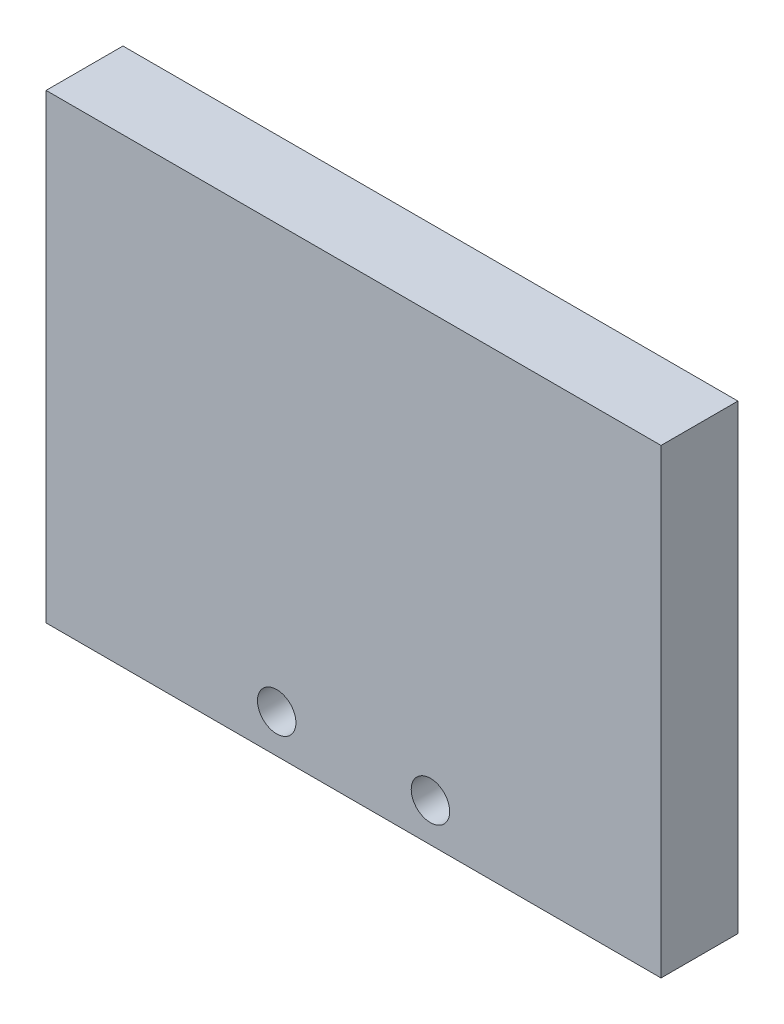
SolidWorks part; units mm, degrees
ref_plane "Front Plane" through (0, 0, 0) normal (0, 0, 1) x (1, 0, 0)
ref_plane "Top Plane" through (0, 0, 0) normal (0, 1, 0) x (1, 0, 0)
ref_plane "Right Plane" through (0, 0, 0) normal (1, 0, 0) x (0, 0, -1)
sketch "Sketch1" plane through (0, 0, 0) normal (0, 0, 1) x (1, 0, 0)
  line L1 (-57.5851, 19.8139) -> (22.4149, 19.8139)
  line L2 (-57.5851, 19.8139) -> (-57.5851, -40.1861)
  line L3 (-57.5851, -40.1861) -> (22.4149, -40.1861)
  line L4 (22.4149, 19.8139) -> (22.4149, -40.1861)
  dimension "D1" = 80
  dimension "D2" = 60
extrude "Boss-Extrude1" add sketch "Sketch1" along normal blind 10
sketch "Sketch2" plane through (0, 0, 10) normal (0, 0, 1) x (1, 0, 0)
  line L0 (-17.5851, 19.8139) -> (-17.5851, -40.1861) construction
  line L1 (22.4149, 19.8139) -> (-57.5851, 19.8139) construction
  line L2 (-57.5851, -40.1861) -> (22.4149, -40.1861) construction
  circle A0 centre (-27.5851, -35.1861) radius 2.5
  circle A1 centre (-7.5851, -35.1861) radius 2.5
  dimension "D1" = 5
  dimension "D2" = 20
  dimension "D3" = 5
extrude "Cut-Extrude1" cut sketch "Sketch2" against normal blind 10
sketch "Sketch3" plane through (0, 0, 10) normal (0, 0, 1) x (1, 0, 0)
  line L0 (-22.5851, -5.6861) -> (-12.5851, -5.6861)
  line L1 (22.4149, 19.8139) -> (-57.5851, 19.8139) construction
  line L2 (-22.5851, -6.1861) -> (-12.5851, -6.1861)
  line L3 (-22.5851, -6.6861) -> (-12.5851, -6.6861)
  line L4 (-22.5851, -7.1861) -> (-12.5851, -7.1861)
  line L5 (-22.5851, -7.6861) -> (-12.5851, -7.6861)
  line L6 (-22.5851, -8.1861) -> (-12.5851, -8.1861)
  line L7 (-22.5851, -8.6861) -> (-12.5851, -8.6861)
  line L8 (-22.5851, -9.1861) -> (-12.5851, -9.1861)
  line L9 (-22.5851, -9.6861) -> (-12.5851, -9.6861)
  line L10 (-22.5851, -10.1861) -> (-12.5851, -10.1861)
  line L11 (-22.5851, -10.6861) -> (-12.5851, -10.6861)
  line L12 (-22.5851, -11.1861) -> (-12.5851, -11.1861)
  line L13 (-22.5851, -11.6861) -> (-12.5851, -11.6861)
  line L14 (-22.5851, -12.1861) -> (-12.5851, -12.1861)
  line L15 (-22.5851, -12.6861) -> (-12.5851, -12.6861)
  line L16 (-22.5851, -13.1861) -> (-12.5851, -13.1861)
  line L17 (-22.5851, -13.6861) -> (-12.5851, -13.6861)
  line L18 (-22.5851, -14.1861) -> (-12.5851, -14.1861)
  line L19 (-22.5851, -14.6861) -> (-12.5851, -14.6861)
  line L20 (-22.5851, -15.1861) -> (-12.5851, -15.1861)
  line L21 (-57.5851, -10.1861) -> (22.4149, -10.1861) construction
  line L22 (-57.5851, 19.8139) -> (-57.5851, -40.1861) construction
  line L23 (22.4149, -40.1861) -> (22.4149, 19.8139) construction
  line L24 (-22.5851, -5.1861) -> (-22.5851, -15.1861)
  line L25 (-22.0851, -5.1861) -> (-22.0851, -15.1861)
  line L26 (-21.5851, -5.1861) -> (-21.5851, -15.1861)
  line L27 (-21.0851, -5.1861) -> (-21.0851, -15.1861)
  line L28 (-20.5851, -5.1861) -> (-20.5851, -15.1861)
  line L29 (-20.0851, -5.1861) -> (-20.0851, -15.1861)
  line L30 (-19.5851, -5.1861) -> (-19.5851, -15.1861)
  line L31 (-19.0851, -5.1861) -> (-19.0851, -15.1861)
  line L32 (-18.5851, -5.1861) -> (-18.5851, -15.1861)
  line L33 (-18.0851, -5.1861) -> (-18.0851, -15.1861)
  line L34 (-17.5851, -5.1861) -> (-17.5851, -15.1861)
  line L35 (-17.0851, -5.1861) -> (-17.0851, -15.1861)
  line L36 (-16.5851, -5.1861) -> (-16.5851, -15.1861)
  line L37 (-16.0851, -5.1861) -> (-16.0851, -15.1861)
  line L38 (-15.5851, -5.1861) -> (-15.5851, -15.1861)
  line L39 (-15.0851, -5.1861) -> (-15.0851, -15.1861)
  line L40 (-14.5851, -5.1861) -> (-14.5851, -15.1861)
  line L41 (-14.0851, -5.1861) -> (-14.0851, -15.1861)
  line L42 (-13.5851, -5.1861) -> (-13.5851, -15.1861)
  line L43 (-13.0851, -5.1861) -> (-13.0851, -15.1861)
  line L84 (-8.3004, -17.5715) -> (-8.3004, -22.5715)
  line L85 (-5.0504, -17.5715) -> (-5.0504, -22.5715)
  line L86 (-4.3004, -17.5715) -> (-4.3004, -22.5715)
  line L87 (-4.8004, -17.5715) -> (-4.8004, -22.5715)
  line L88 (-7.5504, -17.5715) -> (-7.5504, -22.5715)
  line L89 (-8.5504, -17.5715) -> (-8.5504, -22.5715)
  line L90 (-9.0504, -22.0715) -> (-4.0504, -22.0715)
  line L91 (-7.8004, -17.5715) -> (-7.8004, -22.5715)
  line L92 (-9.0504, -18.0715) -> (-4.0504, -18.0715)
  line L93 (-9.0504, -17.8215) -> (-4.0504, -17.8215)
  line L94 (-9.0504, -21.8215) -> (-4.0504, -21.8215)
  line L95 (-4.5504, -17.5715) -> (-4.5504, -22.5715)
  line L96 (-9.0504, -21.0715) -> (-4.0504, -21.0715)
  line L97 (-9.0504, -21.5715) -> (-4.0504, -21.5715)
  line L98 (-9.0504, -22.3215) -> (-4.0504, -22.3215)
  line L99 (-9.0504, -20.5715) -> (-4.0504, -20.5715)
  line L100 (-9.0504, -20.8215) -> (-4.0504, -20.8215)
  line L101 (-9.0504, -19.0715) -> (-4.0504, -19.0715)
  line L102 (-9.0504, -19.5715) -> (-4.0504, -19.5715)
  line L103 (-9.0504, -20.3215) -> (-4.0504, -20.3215)
  line L104 (-8.8004, -17.5715) -> (-8.8004, -22.5715)
  line L105 (-9.0504, -18.3215) -> (-4.0504, -18.3215)
  line L106 (-9.0504, -18.8215) -> (-4.0504, -18.8215)
  line L107 (-6.8004, -17.5715) -> (-6.8004, -22.5715)
  line L108 (-9.0504, -19.8215) -> (-4.0504, -19.8215)
  line L109 (-8.0504, -17.5715) -> (-8.0504, -22.5715)
  line L110 (-6.0504, -17.5715) -> (-6.0504, -22.5715)
  line L111 (-9.0504, -18.5715) -> (-4.0504, -18.5715)
  line L112 (-9.0504, -19.3215) -> (-4.0504, -19.3215)
  line L113 (-9.0504, -22.5715) -> (-4.0504, -22.5715)
  line L114 (-5.8004, -17.5715) -> (-5.8004, -22.5715)
  line L115 (-6.5504, -17.5715) -> (-6.5504, -22.5715)
  line L116 (-6.3004, -17.5715) -> (-6.3004, -22.5715)
  line L117 (-5.3004, -17.5715) -> (-5.3004, -22.5715)
  line L118 (-9.0504, -17.5715) -> (-9.0504, -22.5715)
  line L119 (-7.0504, -17.5715) -> (-7.0504, -22.5715)
  line L120 (-7.3004, -17.5715) -> (-7.3004, -22.5715)
  line L121 (-9.0504, -21.3215) -> (-4.0504, -21.3215)
  line L122 (-5.5504, -17.5715) -> (-5.5504, -22.5715)
  line L123 (-9.0504, -20.0715) -> (-4.0504, -20.0715)
  circle A0 centre (-13.0851, -5.6861) radius 0.25
  circle A1 centre (-13.0851, -5.6861) radius 0.5
  circle A2 centre (-13.0851, -5.6861) radius 0.75
  circle A6 centre (-4.3004, -17.8215) radius 0.25
  circle A7 centre (-4.3004, -17.8215) radius 0.125
  circle A8 centre (-4.3004, -17.8215) radius 0.375
  point P4 (-17.5851, -5.6861)
  point P5 (-17.5851, 19.8139)
  point P97 (27.5481, 4)
  dimension "D9" = 0.5
  dimension "D10" = 1
  dimension "D11" = 1.5
  dimension "D1" = 10
  dimension "D3" = 0.5
  dimension "D4" = 10
  dimension "D8" = 0.5
  dimension "D2" = 20
  dimension "D6" = 20
